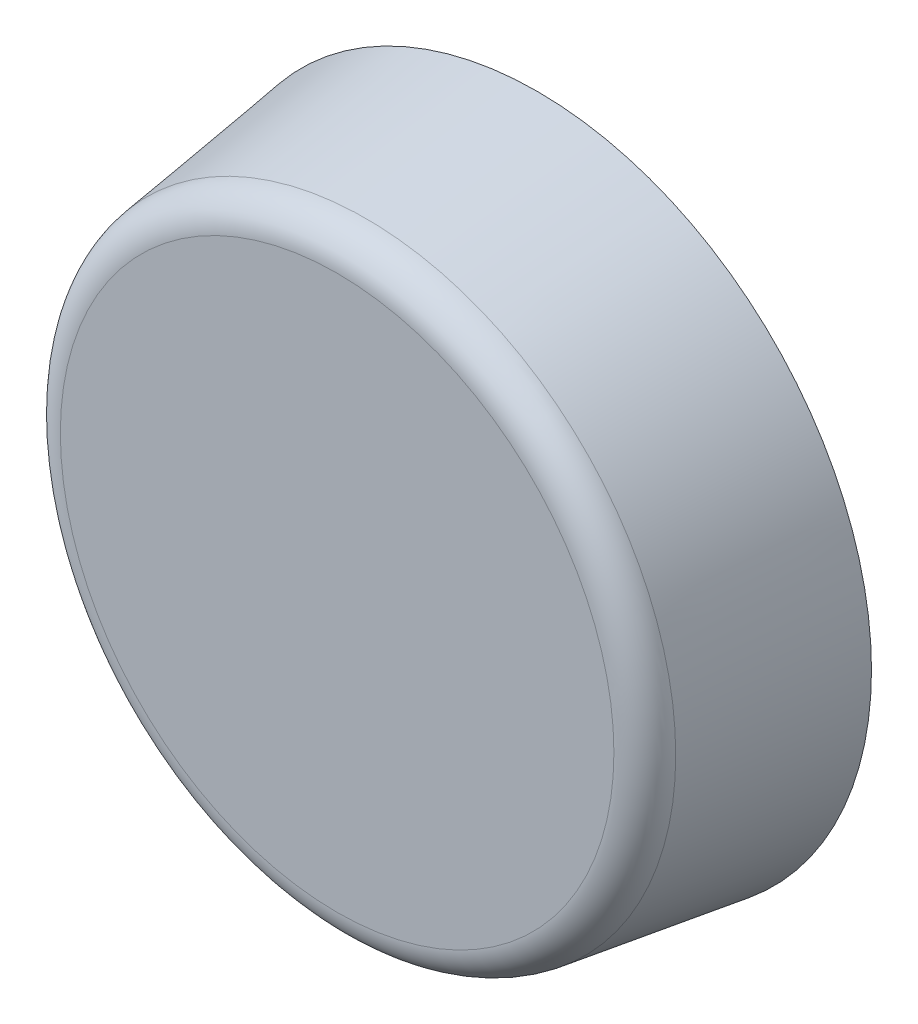
SolidWorks part; units mm, degrees
ref_plane "Plan de face" through (0, 0, 0) normal (0, 0, 1) x (1, 0, 0)
ref_plane "Plan de dessus" through (0, 0, 0) normal (0, 1, 0) x (1, 0, 0)
ref_plane "Plan de droite" through (0, 0, 0) normal (1, 0, 0) x (0, 0, -1)
sketch "Esquisse1" plane through (0, 0, 0) normal (0, 0, 1) x (1, 0, 0)
  circle A0 centre (0, 0) radius 4.05
  dimension "D1" = 8.1
extrude "Boss.-Extru.1" add sketch "Esquisse1" along normal blind 2
sketch "Esquisse2" plane through (0, 0, 2) normal (0, 0, 1) x (1, 0, 0)
  circle A0 centre (0, 0) radius 10
  dimension "D1" = 20
extrude "Boss.-Extru.2" add sketch "Esquisse2" along normal blind 6 draft 8
fillet "Congé1" radius 1 1 edges at (9.1568, 0, 8)
